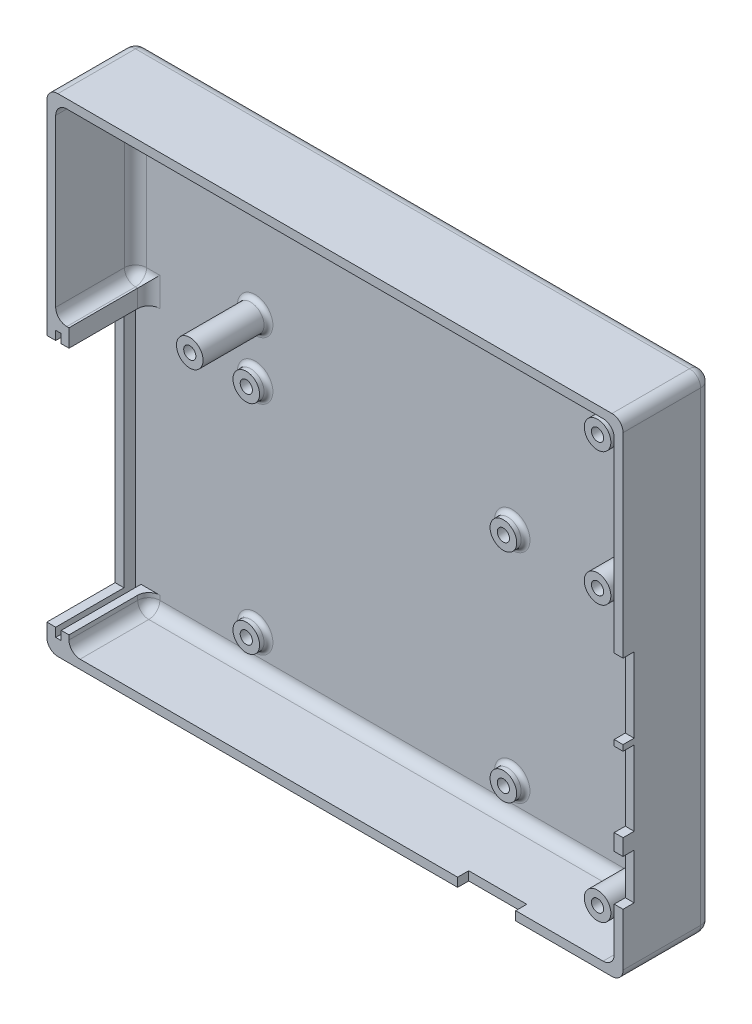
SolidWorks part; units mm, degrees
ref_plane "Plan de face" through (0, 0, 0) normal (0, 0, 1) x (1, 0, 0)
ref_plane "Plan de dessus" through (0, 0, 0) normal (0, 1, 0) x (1, 0, 0)
ref_plane "Plan de droite" through (0, 0, 0) normal (1, 0, 0) x (0, 0, -1)
sketch "Esquisse1" plane through (0, 0, 0) normal (0, 0, 1) x (1, 0, 0)
  line L1 (-87.7373, 71.0214) -> (42.2627, 71.0214)
  line L2 (-87.7373, 71.0214) -> (-87.7373, -38.9786)
  line L3 (-87.7373, -38.9786) -> (42.2627, -38.9786)
  line L4 (42.2627, 71.0214) -> (42.2627, -38.9786)
  dimension "D1" = 110
  dimension "D2" = 130
extrude "Boss.-Extru.1" add sketch "Esquisse1" along normal blind 2
sketch "Esquisse3" plane through (0, 0, 2) normal (0, 0, 1) x (1, 0, 0)
  line L2 (-87.7373, 71.0214) -> (-87.7373, -38.9786) construction
  line L3 (-87.7373, -38.9786) -> (42.2627, -38.9786) construction
  line L4 (42.2627, 71.0214) -> (-87.7373, 71.0214) construction
  circle A0 centre (33.2627, 62.0214) radius 1.375
  circle A1 centre (33.2627, 32.0214) radius 1.375
  circle A2 centre (33.2627, -29.9786) radius 1.375
  circle A3 centre (-58.7373, -29.9786) radius 1.375
  circle A4 centre (-0.7373, -29.9786) radius 1.375
  circle A5 centre (-0.7373, 19.0214) radius 1.375
  circle A6 centre (-58.7373, 19.0214) radius 1.375
  circle A7 centre (-58.7373, 32.0214) radius 1.375
  circle A8 centre (-58.7373, -29.9786) radius 3
  circle A9 centre (-0.7373, -29.9786) radius 3
  circle A10 centre (33.2627, -29.9786) radius 3
  circle A11 centre (-0.7373, 19.0214) radius 3
  circle A12 centre (33.2627, 32.0214) radius 3
  circle A13 centre (-58.7373, 32.0214) radius 3
  circle A14 centre (-58.7373, 19.0214) radius 3
  circle A15 centre (33.2627, 62.0214) radius 3
  dimension "D1" = 2.75
  dimension "D2" = 2.75
  dimension "D3" = 2.75
  dimension "D4" = 2.75
  dimension "D5" = 2.75
  dimension "D6" = 2.75
  dimension "D7" = 2.75
  dimension "D8" = 2.75
  dimension "D27" = 6
  dimension "D28" = 6
  dimension "D29" = 6
  dimension "D30" = 6
  dimension "D31" = 6
  dimension "D32" = 6
  dimension "D33" = 6
  dimension "D34" = 6
  dimension "D9" = 58
  dimension "D10" = 92
  dimension "D11" = 29
  dimension "D12" = 9
  dimension "D13" = 9
  dimension "D14" = 9
  dimension "D15" = 49
  dimension "D16" = 29
  dimension "D17" = 29
  dimension "D18" = 62
  dimension "D19" = 58
  dimension "D20" = 49
  dimension "D21" = 92
  dimension "D22" = 62
  dimension "D23" = 92
  dimension "D24" = 92
  dimension "D25" = 110
  dimension "D26" = 9
extrude "Boss.-Extru.2" add sketch "Esquisse3" along normal blind 2
sketch "Esquisse4" plane through (0, 0, 2) normal (0, 0, 1) x (1, 0, 0)
  circle A0 centre (-58.7373, 32.0214) radius 3
  circle A1 centre (-58.7373, 32.0214) radius 1.375
  circle A2 centre (33.2627, 62.0214) radius 3
  circle A3 centre (33.2627, 62.0214) radius 1.375
  circle A4 centre (33.2627, 32.0214) radius 1.375
  circle A5 centre (33.2627, 32.0214) radius 3
  circle A6 centre (33.2627, -29.9786) radius 3
  circle A7 centre (33.2627, -29.9786) radius 1.375
extrude "Boss.-Extru.3" add sketch "Esquisse4" along normal blind 14.75
fillet "Congé1" radius 1 8 edges at (36.2627, 62.0214, 2) (36.2627, 32.0214, 2) (-55.7373, -29.9786, 2) (36.2627, -29.9786, 2) (2.2627, -29.9786, 2) (2.2627, 19.0214, 2) (-55.7373, 19.0214, 2) (-55.7373, 32.0214, 2)
sketch "Esquisse5" plane through (0, 0, 2) normal (0, 0, 1) x (1, 0, 0)
  line L1 (-87.7373, 71.0214) -> (42.2627, 71.0214)
  line L2 (-87.7373, 71.0214) -> (-87.7373, -38.9786)
  line L3 (-87.7373, -38.9786) -> (42.2627, -38.9786)
  line L4 (42.2627, 71.0214) -> (42.2627, -38.9786)
  line L5 (-85.7373, 69.0214) -> (40.2627, 69.0214)
  line L6 (-85.7373, 69.0214) -> (-85.7373, -36.9786)
  line L7 (-85.7373, -36.9786) -> (40.2627, -36.9786)
  line L8 (40.2627, 69.0214) -> (40.2627, -36.9786)
  dimension "D1" = 2
  dimension "D2" = 2
  dimension "D3" = 2
  dimension "D4" = 2
extrude "Boss.-Extru.5" add sketch "Esquisse5" along normal blind 18
fillet "Congé3" radius 2.5 4 edges at (42.2627, 71.0214, 10) (42.2627, -38.9786, 10) (-87.7373, -38.9786, 10) (-87.7373, 71.0214, 10)
sketch "Esquisse6" plane through (0, 0, 20) normal (0, 0, 1) x (1, 0, 0)
  line L0 (40.2627, -36.9786) -> (40.2627, 69.0214) construction
  line L1 (40.2627, -24.5886) -> (42.2627, -24.5886)
  line L2 (40.2627, -24.5886) -> (40.2627, -14.2886)
  line L3 (40.2627, -14.2886) -> (42.2627, -14.2886)
  line L4 (42.2627, -24.5886) -> (42.2627, -14.2886)
  line L5 (42.2627, -36.4786) -> (42.2627, 68.5214) construction
  line L6 (-85.2373, -38.9786) -> (39.7627, -38.9786) construction
  line L7 (40.2627, -10.6086) -> (42.2627, -10.6086)
  line L8 (40.2627, -10.6086) -> (40.2627, 6.2714)
  line L9 (40.2627, 6.2714) -> (42.2627, 6.2714)
  line L10 (42.2627, -10.6086) -> (42.2627, 6.2714)
  line L11 (40.2627, 7.5814) -> (42.2627, 7.5814)
  line L12 (40.2627, 7.5814) -> (40.2627, 24.4614)
  line L13 (40.2627, 24.4614) -> (42.2627, 24.4614)
  line L14 (42.2627, 7.5814) -> (42.2627, 24.4614)
  line L15 (-85.7373, -36.9786) -> (40.2627, -36.9786) construction
  line L16 (4.9427, -36.9786) -> (18.0427, -36.9786)
  line L17 (4.9427, -36.9786) -> (4.9427, -38.9786)
  line L18 (4.9427, -38.9786) -> (18.0427, -38.9786)
  line L19 (18.0427, -36.9786) -> (18.0427, -38.9786)
  point P16 (41.2627, -24.5886)
  dimension "D1" = 14.39
  dimension "D2" = 24.69
  dimension "D3" = 28.37
  dimension "D4" = 45.25
  dimension "D5" = 46.56
  dimension "D6" = 63.44
  dimension "D7" = 37.32
  dimension "D8" = 24.22
extrude "Enlèv. mat.-Extru.1" cut sketch "Esquisse6" against normal blind 2.5
sketch "Esquisse7" plane through (0, 0, 20) normal (0, 0, 1) x (1, 0, 0)
  line L0 (-85.7373, 69.0214) -> (-85.7373, -36.9786) construction
  line L1 (-85.7373, -33.4786) -> (-87.7373, -33.4786)
  line L2 (-85.7373, -33.4786) -> (-85.7373, 22.5214)
  line L3 (-85.7373, 22.5214) -> (-87.7373, 22.5214)
  line L4 (-87.7373, -33.4786) -> (-87.7373, 22.5214)
  line L7 (-85.7373, -36.9786) -> (4.9427, -36.9786) construction
  dimension "D1" = 3.5
  dimension "D2" = 59.5
extrude "Enlèv. mat.-Extru.2" cut sketch "Esquisse7" against normal blind 15.4
fillet "Congé5" radius 2.5 8 edges at (41.5305, 70.2892, 0) (42.2627, 16.0214, 0) (41.5305, -38.2463, 0) (-22.7373, -38.9786, 0) (-87.005, -38.2463, 0) (-87.7373, 16.0214, 0) (-87.005, 70.2892, 0) (-22.7373, 71.0214, 0)
sketch "Esquisse9" plane through (-85.7373, 0, 0) normal (1, 0, 0) x (0, 0, -1)
  line L0 (-2, 69.0214) -> (-2, -36.9786) construction
  line L1 (-20, 22.5214) -> (-2, 22.5214)
  line L2 (-20, 22.5214) -> (-20, 26.5214)
  line L3 (-20, 26.5214) -> (-2, 26.5214)
  line L4 (-2, 22.5214) -> (-2, 26.5214)
  line L5 (-2, 24.5214) -> (-20, 24.5214)
  line L6 (-20, -33.4786) -> (-2, -33.4786)
  line L7 (-20, -33.4786) -> (-20, -36.9786)
  line L8 (-20, -36.9786) -> (-2, -36.9786)
  line L9 (-2, -33.4786) -> (-2, -36.9786)
  line L10 (-2, -35.4786) -> (-20, -35.4786)
  line M9 (-20, -36.9786) -> (-2, -36.9786)
  line M10 (-2, -36.9786) -> (-2, 69.0214)
  line M12 (-20, 69.0214) -> (-20, 22.5214)
  dimension "D1" = 18
  dimension "D2" = 2
  dimension "D3" = 2
  dimension "D4" = 4
extrude "Boss.-Extru.6" add sketch "Esquisse9" along normal blind 3 contours L5 L4 L3 M12 | L10 L7 M10 M9
sketch "Esquisse11" plane through (0, 24.5214, 0) normal (0, -1, 0) x (1, 0, 0)
  line L0 (-82.7373, 2) -> (-85.7373, 2) construction
  line L1 (-82.7373, 20) -> (-84.4873, 20)
  line L2 (-82.7373, 20) -> (-82.7373, 2)
  line L3 (-82.7373, 2) -> (-84.4873, 2)
  line L4 (-84.4873, 20) -> (-84.4873, 2)
  line L6 (-82.7373, 20) -> (-85.7373, 20)
  line L7 (-82.7373, 20) -> (-82.7373, 2)
  line L8 (-82.7373, 2) -> (-85.7373, 2)
  line L9 (-85.7373, 20) -> (-85.7373, 2)
  line M5 (-85.7373, 2) -> (-82.7373, 2)
  line M6 (-82.7373, 2) -> (-82.7373, 20)
  line M7 (-82.7373, 20) -> (-85.7373, 20)
  dimension "D1" = 1.75
extrude "Boss.-Extru.7" add sketch "Esquisse11" along normal blind 2 contours L4 M7 M5 M6
sketch "Esquisse12" plane through (0, -35.4786, 0) normal (0, 1, 0) x (1, 0, 0)
  line L0 (-84.4873, -2) -> (-84.4873, -20)
  line L1 (-82.7373, -2) -> (-85.7373, -2)
  line L2 (-82.7373, -2) -> (-82.7373, -20)
  line L3 (-82.7373, -20) -> (-85.7373, -20)
  line L4 (-85.7373, -2) -> (-85.7373, -20)
  line M5 (-85.7373, -20) -> (-82.7373, -20)
  line M6 (-82.7373, -20) -> (-82.7373, -2)
  line M7 (-82.7373, -2) -> (-85.7373, -2)
  dimension "D1" = 1.75
extrude "Boss.-Extru.8" add sketch "Esquisse12" along normal blind 2 contours L0 M7 M5 M6
fillet "Congé7" radius 2.5 5 edges at (40.2627, -36.9786, 11) (-82.7373, -36.9786, 11) (-85.7373, 26.5214, 11) (-85.7373, 69.0214, 11) (40.2627, 69.0214, 11)
fillet "Congé8" radius 2.5 11 edges at (-82.7373, -33.9786, 2) (-82.005, -36.2463, 2) (-21.2373, -36.9786, 2) (39.5305, -36.2463, 2) (40.2627, 16.0214, 2) (39.5305, 68.2892, 2) (-22.7373, 69.0214, 2) (-85.005, 68.2892, 2) (-82.9873, 26.5214, 2) (-85.005, 27.2537, 2) (-85.7373, 47.7714, 2)
fillet "Congé9" radius 2.5 1 edges at (-82.7373, 25.7714, 2)
ref_plane "Plan1" through (-80.2373, 29.0214, 2) normal (1, 0, 0) x (0, 0, -1)
